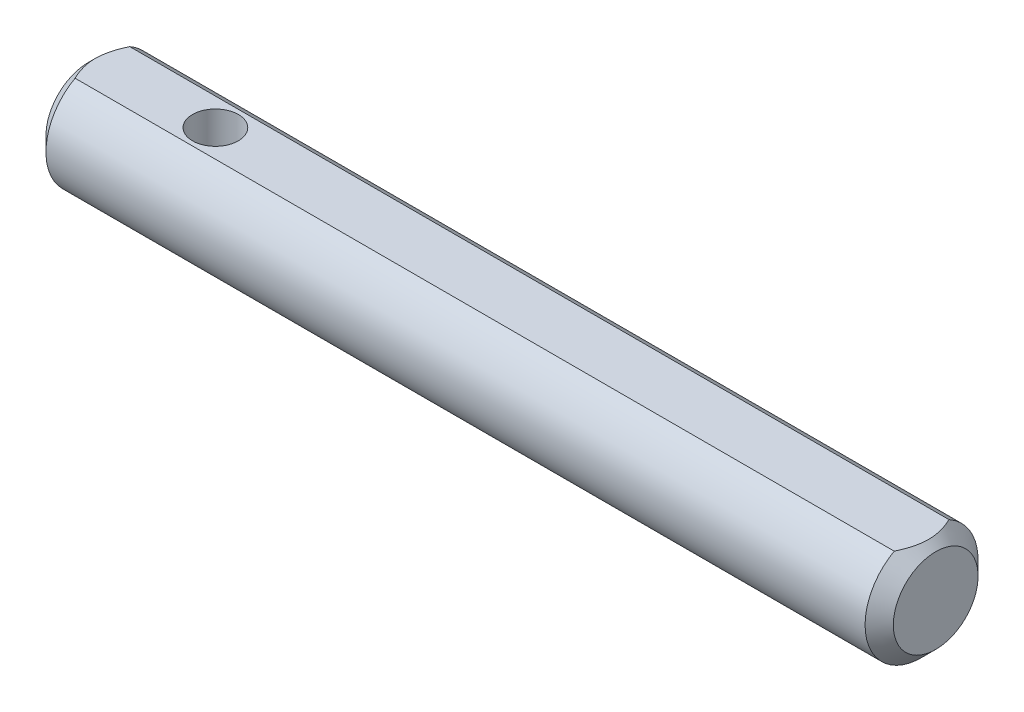
SolidWorks part; units mm, degrees
ref_plane "Front Plane" through (0, 0, 0) normal (0, 0, 1) x (1, 0, 0)
ref_plane "Top Plane" through (0, 0, 0) normal (0, 1, 0) x (1, 0, 0)
ref_plane "Right Plane" through (0, 0, 0) normal (1, 0, 0) x (0, 0, -1)
sketch "Sketch1" plane through (0, 0, 0) normal (0, 0, 1) x (1, 0, 0)
  line L0 (0, 0) -> (60, 0)
  line L1 (0, 0) -> (60, 0) construction
  line L2 (0, 0) -> (0, 4)
  line L3 (0, 4) -> (60, 4)
  line L4 (60, 0) -> (60, 4)
  dimension "MSM_70" = 8
  dimension "W" = 60
revolve "Revolve1" add sketch "Sketch1" angle 360 about L1
chamfer "Chamfer1" distance 1 2 edges at (60, 0, 4) (0, 0, 4)
sketch "Sketch2" plane through (0, 0, 0) normal (1, 0, 0) x (0, 0, -1)
  line L0 (-1.9365, 3.5) -> (1.9365, 3.5)
  arc A0 (1.9365, 3.5) -> (-1.9365, 3.5) centre (0, 0) ccw
  dimension "MSM_70" = 8
  dimension "MSM_71" = 3.5
extrude "Cut-Extrude1" cut sketch "Sketch2" along normal through all
hole_wizard "Tap1" positions "Sketch4" profile "Sketch3" hole size "M1x0.25" standard "JIS" end condition through all
sketch "Sketch4" plane through (0, 3.5, 0) normal (0, 1, 0) x (1, 0, 0)
  point P0 (9, 0)
  dimension "FIX_4" = 9
sketch "Sketch3" plane through (9, 3.5, 0) normal (1, 0, 0) x (0, 0, 1)
  line L0 (0, 0) -> (0, 7.5)
  line L1 (0, 7.5) -> (1.621, 7.5)
  line L2 (1.621, 7.5) -> (1.621, 0)
  line L5 (1.621, 0) -> (0, 0)
  line L11 (0, -6.35) -> (0, 107.95) construction
  dimension "STD_3" = 3.242
  dimension "Thru Hole Depth" = 7.5
cosmetic thread "Thread1" parameters "HTD_1"=4
